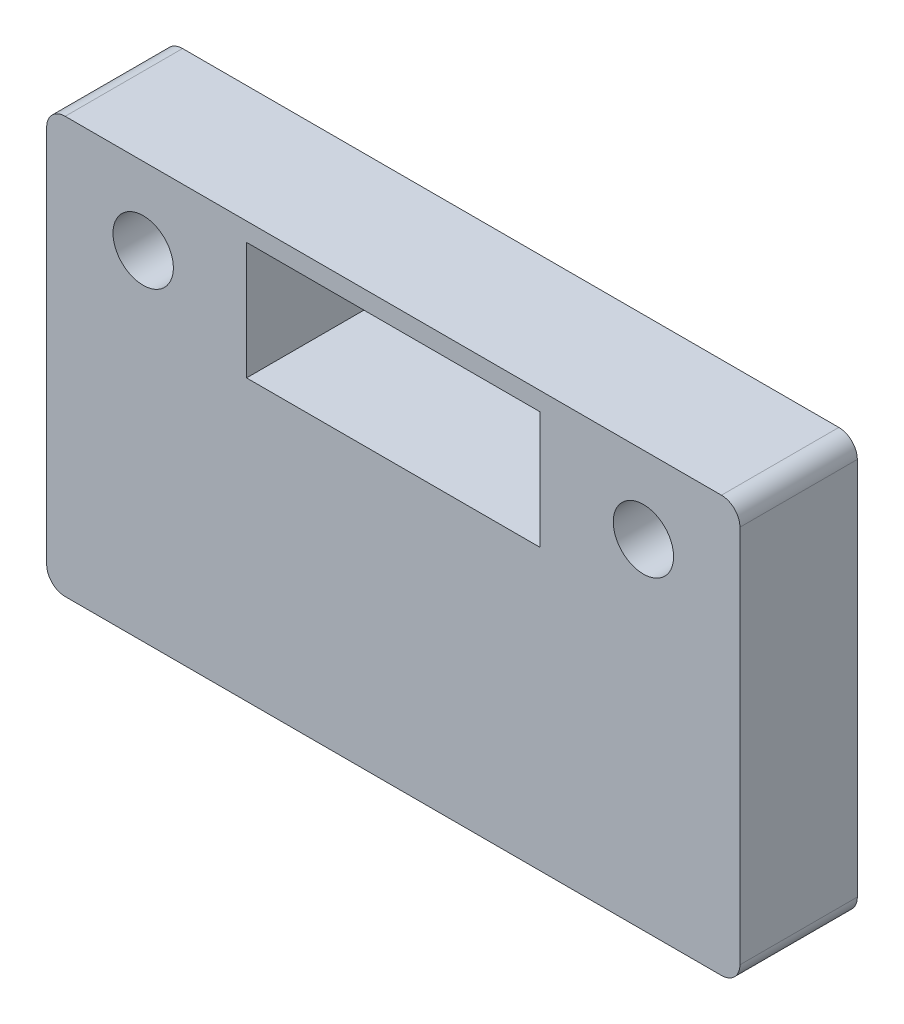
SolidWorks part; units mm, degrees
ref_plane "Front Plane" through (0, 0, 0) normal (0, 0, 1) x (1, 0, 0)
ref_plane "Top Plane" through (0, 0, 0) normal (0, 1, 0) x (1, 0, 0)
ref_plane "Right Plane" through (0, 0, 0) normal (1, 0, 0) x (0, 0, -1)
sketch "Sketch1" plane through (0, 0, 0) normal (0, 0, 1) x (1, 0, 0)
  line L0 (37.5, -2) -> (53.375, -2)
  line L1 (0, 0) -> (75, 0)
  line L2 (0, 0) -> (0, -45)
  line L3 (0, -45) -> (75, -45)
  line L4 (75, 0) -> (75, -45)
  line L5 (53.375, -2) -> (53.375, -14.7)
  line L6 (53.375, -14.7) -> (21.625, -14.7)
  line L7 (21.625, -14.7) -> (21.625, -2)
  line L8 (21.625, -2) -> (37.5, -2)
  dimension "D1" = 75
  dimension "D2" = 45
  dimension "D3" = 12.7
  dimension "D4" = 2
  dimension "D5" = 31.75
  dimension "D6" = 37.5
extrude "Boss-Extrude1" add sketch "Sketch1" along normal blind 12.7
sketch "Sketch2" plane through (0, 0, 0) normal (0, 0, -1) x (-1, 0, 0)
  line L0 (-75, -8.35) -> (-64.56, -8.35)
  line L1 (-75, -45) -> (-75, 0) construction
  line L2 (0, -8.35) -> (-10.44, -8.35)
  line L3 (0, 0) -> (0, -45) construction
  dimension "D1" = 10.44
  dimension "D2" = 10.44
hole_wizard "CSK for 1/4 Flat Head Machine Screw2" positions "Sketch5" profile "Sketch6" countersink size "1/4" standard "ANSI Inch" end condition through all
sketch "Sketch5" plane through (0, 0, 0) normal (0, 0, -1) x (-1, 0, 0)
  point P0 (-64.56, -8.35)
  point P3 (-10.44, -8.35)
sketch "Sketch6" plane through (64.56, -8.35, 0) normal (1, 0, 0) x (0, 1, 0)
  line L0 (0, 0) -> (0, 12.7)
  line L1 (0, 12.7) -> (3.2639, 12.7)
  line L2 (3.2639, 12.7) -> (3.2639, 3.6524)
  line L3 (3.2639, 3.6524) -> (6.4389, 0)
  line L5 (6.4389, 0) -> (0, 0)
  line L6 (-3.2639, 3.6524) -> (-6.4389, 0) construction
  line L11 (0, -6.35) -> (0, 107.95) construction
  dimension "Thru Hole Dia." = 6.5278
  dimension "Thru Hole Depth" = 12.7
  dimension "Near C'Sink Dia." = 12.8778
  dimension "Near C'Sink Angle" = 82
fillet "Fillet1" radius 2 2 edges at (0, 0, 6.35) (0, -45, 6.35)
fillet "Fillet2" radius 2 2 edges at (75, -45, 6.35) (75, 0, 6.35)
